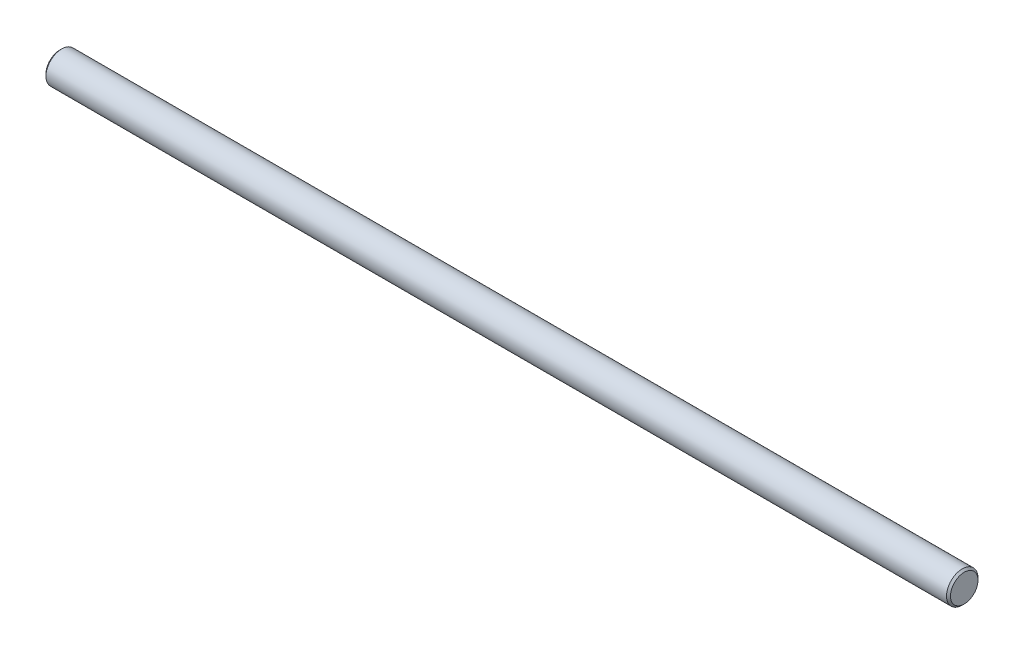
SolidWorks part; units mm, degrees
ref_plane "Front Plane" through (0, 0, 0) normal (0, 0, 1) x (1, 0, 0)
ref_plane "Top Plane" through (0, 0, 0) normal (0, 1, 0) x (1, 0, 0)
ref_plane "Right Plane" through (0, 0, 0) normal (1, 0, 0) x (0, 0, -1)
sketch "Sketch1" plane through (0, 0, 0) normal (1, 0, 0) x (0, 0, -1)
  circle A0 centre (0, 0) radius 4
  dimension "D1" = 8
extrude "Boss-Extrude1" add sketch "Sketch1" along normal mid plane 230
chamfer "Chamfer1" distance 0.5 angle 45 2 edges at (-115, 0, -4) (115, 0, -4)
